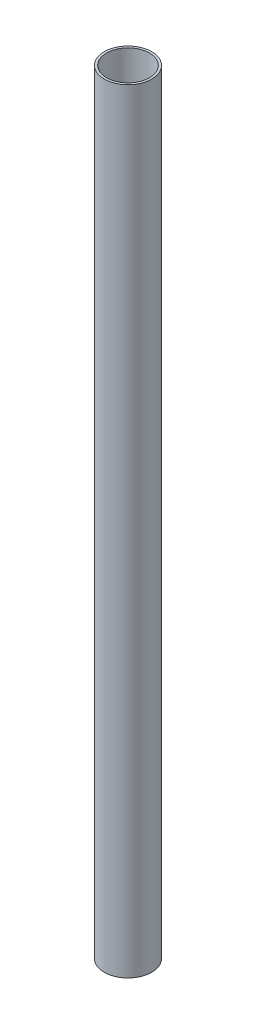
SolidWorks part; units mm, degrees
material "AISI 4130 Steel, annealed at 865C"
ref_plane "X-Y Datum" through (0, 0, 0) normal (0, 0, 1) x (1, 0, 0)
ref_plane "X-Z Datum" through (0, 0, 0) normal (0, 1, 0) x (1, 0, 0)
ref_plane "Y-Z Datum" through (0, 0, 0) normal (1, 0, 0) x (0, 0, -1)
sketch "Sketch1" plane through (0, 0, 0) normal (0, 1, 0) x (1, 0, 0)
  circle A0 centre (0, 0) radius 12.7
  circle A1 centre (0, 0) radius 11.4935
  dimension "D1" = 25.4
  dimension "D2" = 22.987
extrude "Boss-Extrude1" add sketch "Sketch1" along normal blind 414.02
